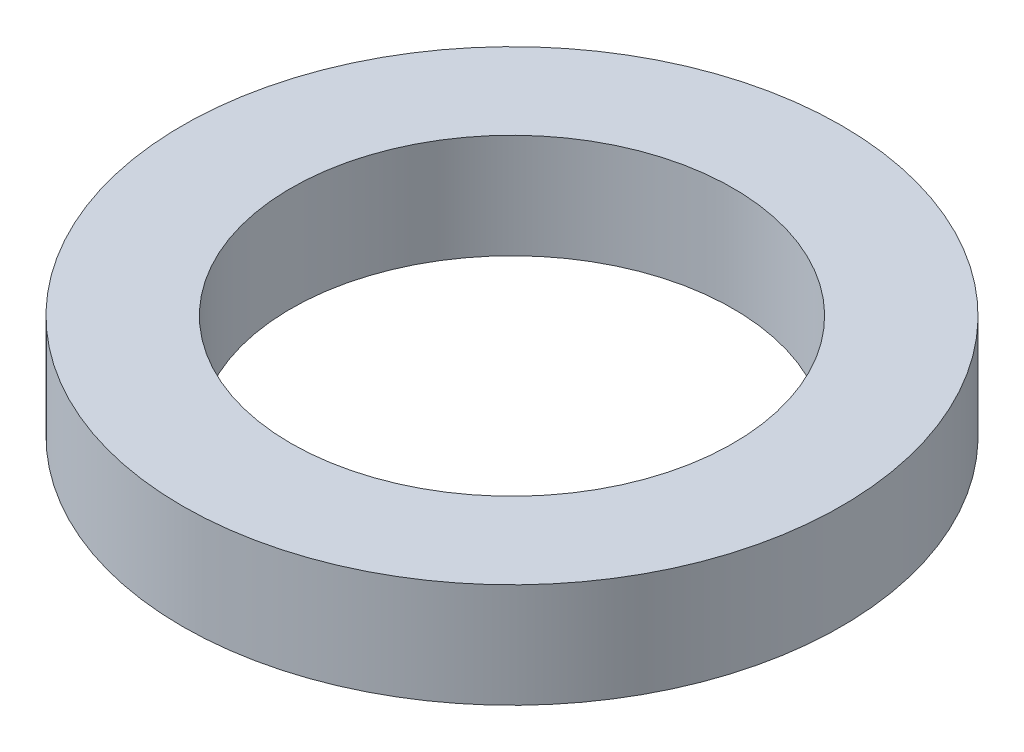
SolidWorks part; units mm, degrees
ref_plane "Plan de face" through (0, 0, 0) normal (0, 0, 1) x (1, 0, 0)
ref_plane "Plan de dessus" through (0, 0, 0) normal (0, 1, 0) x (1, 0, 0)
ref_plane "Plan de droite" through (0, 0, 0) normal (1, 0, 0) x (0, 0, -1)
ref_plane "Plan1" through (0, 0, 0) normal (0, 0, -1) x (-1, 0, 0)
sketch "Esquisse1" plane through (0, 0, 0) normal (0, 0, -1) x (-1, 0, 0)
  line L0 (-4.025, 1.9) -> (-6, 1.9)
  line L1 (-6, 1.9) -> (-6, 0)
  line L2 (-6, 0) -> (-4.025, 0)
  line L3 (-4.025, 0) -> (-4.025, 1.9)
  line L4 (0, 0) -> (0, 1.9) construction
revolve "Révolution1" add sketch "Esquisse1" angle 360 about L4
